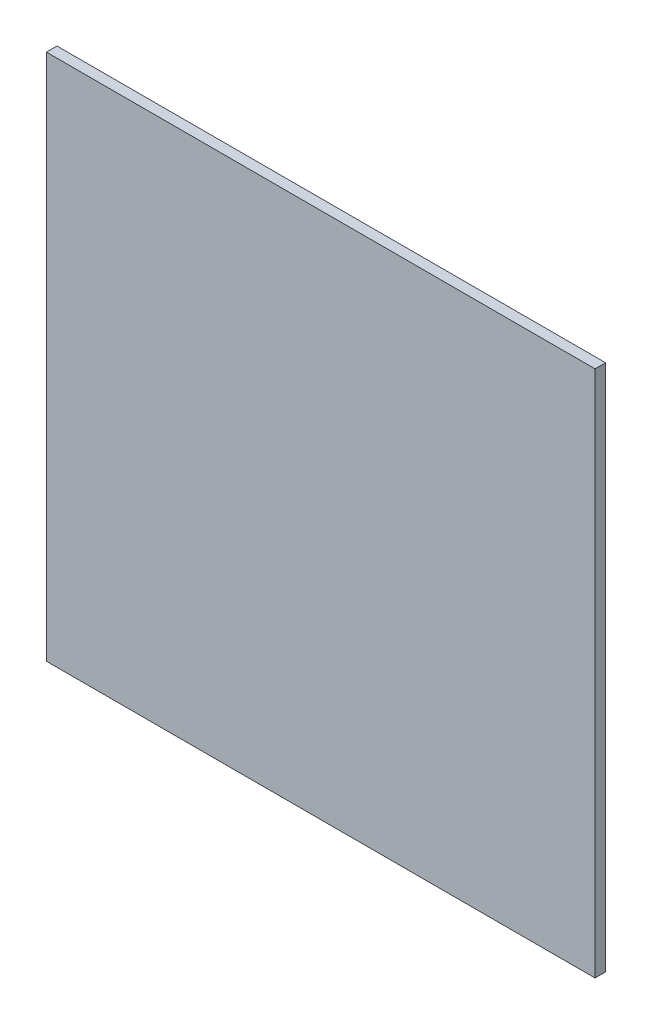
SolidWorks part; units mm, degrees
material "Plain Carbon Steel"
ref_plane "Front Plane" through (0, 0, 0) normal (0, 0, 1) x (1, 0, 0)
ref_plane "Top Plane" through (0, 0, 0) normal (0, 1, 0) x (1, 0, 0)
ref_plane "Right Plane" through (0, 0, 0) normal (1, 0, 0) x (0, 0, -1)
sketch "Sketch1" plane through (0, 0, 118.3406) normal (0, 0, 1) x (1, 0, 0)
  line L0 (-45.8036, 165.4353) -> (-51.8036, 165.4353) construction
  line L1 (-51.8036, 165.4353) -> (260.1964, 165.4353)
  line L2 (-51.8036, 165.4353) -> (-51.8036, -134.5647)
  line L3 (-51.8036, -134.5647) -> (260.1964, -134.5647)
  line L4 (260.1964, 165.4353) -> (260.1964, -134.5647)
extrude "Boss-Extrude1" add sketch "Sketch1" along normal blind 6
